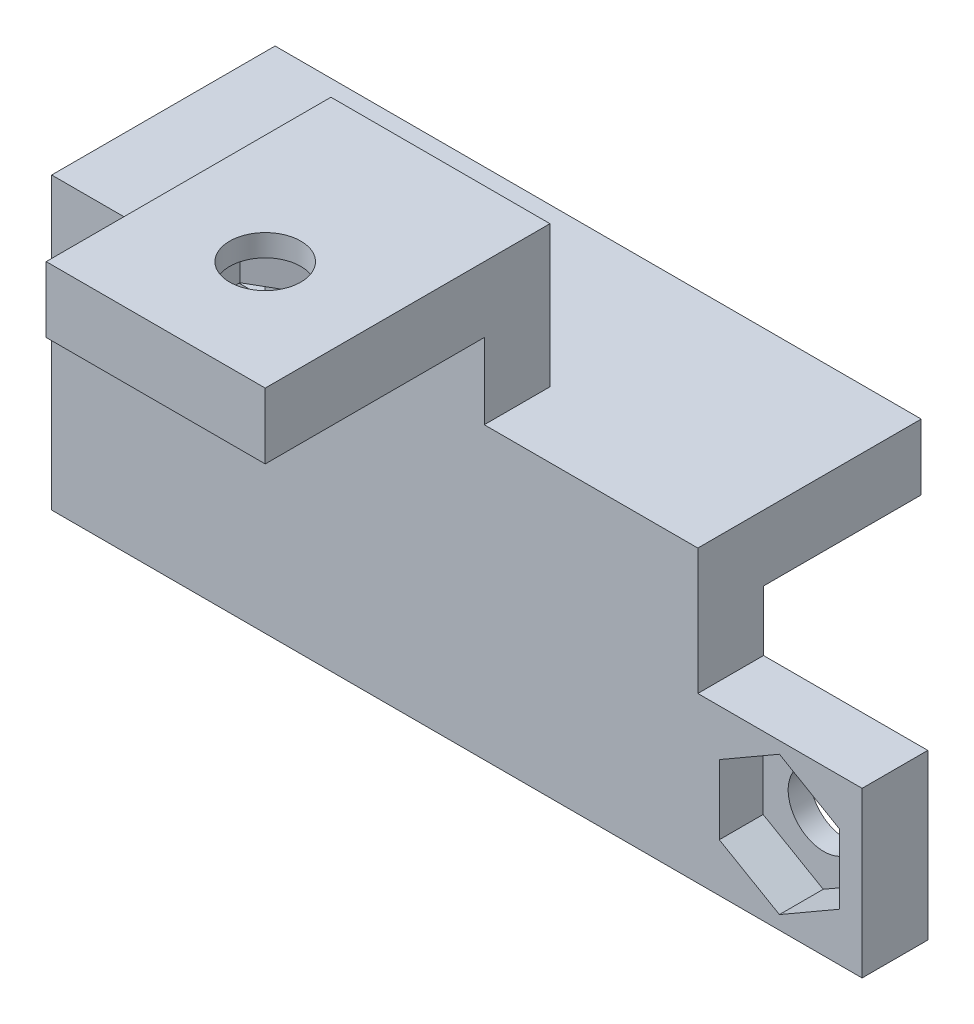
SolidWorks part; units mm, degrees
ref_plane "Alzado" through (0, 0, 0) normal (0, 0, 1) x (1, 0, 0)
ref_plane "Planta" through (0, 0, 0) normal (0, 1, 0) x (1, 0, 0)
ref_plane "Vista lateral" through (0, 0, 0) normal (1, 0, 0) x (0, 0, -1)
sketch "Croquis1" plane through (0, 0, 0) normal (0, 0, 1) x (1, 0, 0)
  line L0 (-40.4588, -20.95) -> (-40.4588, -24.7) construction
  line L1 (-40.4588, -24.7) -> (-77.4588, -24.7)
  line L2 (-77.4588, -14.45) -> (-47.9588, -14.45)
  line L4 (-40.4588, -24.7) -> (-40.4588, -17.2)
  line L5 (-40.4588, -17.2) -> (-47.9588, -17.2)
  line L7 (-47.9588, -17.2) -> (-47.9588, -14.45)
  line L8 (-77.4588, -24.7) -> (-77.4588, -14.45)
  circle A0 centre (-44.2088, -20.95) radius 1.625
  dimension "D1" = 3.25
  dimension "D2" = 40.4588
  dimension "D3" = 44.2088
  dimension "D4" = 47.9588
  dimension "D5" = 77.4588
  dimension "D6" = 14.45
  dimension "D7" = 17.2
extrude "Saliente-Extruir1" add sketch "Croquis1" along normal blind 3
sketch "Croquis2" plane through (0, 0, 3) normal (0, 0, 1) x (1, 0, 0)
  line L0 (-40.4588, -24.7) -> (-40.4588, -17.2) construction
  line L1 (-44.2325, -17.739) -> (-46.9778, -19.324)
  line L2 (-46.9778, -19.324) -> (-46.9778, -22.494)
  line L3 (-46.9778, -22.494) -> (-44.2325, -24.079)
  line L4 (-44.2325, -24.079) -> (-41.4872, -22.494)
  line L5 (-41.4872, -22.494) -> (-41.4872, -19.324)
  line L6 (-41.4872, -19.324) -> (-44.2325, -17.739)
  line L7 (-47.9588, -14.45) -> (-77.4588, -14.45) construction
  circle A0 centre (-44.2325, -20.909) radius 2.7453 construction
  dimension "D1" = 5.4906
  dimension "D2" = 1.0284
  dimension "D3" = 3.289
extrude "Cortar-Extruir1" cut sketch "Croquis2" against normal blind 2
sketch "Croquis4" plane through (0, -14.45, 0) normal (0, 1, 0) x (1, 0, 0)
  line L0 (-77.3588, 7.2) -> (-77.4588, 7.2) construction
  line L1 (-77.4588, -3) -> (-77.4588, 0) construction
  line L2 (-47.9588, -3) -> (-77.4588, -3)
  line L3 (-47.9588, -3) -> (-47.9588, 7.2)
  line L4 (-47.9588, 7.2) -> (-77.4588, 7.2)
  line L5 (-77.4588, -3) -> (-77.4588, 7.2)
  line L6 (-47.9588, 0) -> (-77.4588, 0) construction
  dimension "D1" = 29.5
  dimension "D2" = 7.2
  dimension "D3" = 3
extrude "Saliente-Extruir2" add sketch "Croquis4" along normal blind 3
sketch "Croquis6" plane through (0, 0, 3) normal (0, 0, 1) x (1, 0, 0)
  line L0 (-77.4588, -11.45) -> (-47.9588, -11.45) construction
  line L1 (-47.9588, -11.45) -> (-62.7088, -11.45) construction
  line L2 (-47.9588, -17.2) -> (-47.9588, -11.45) construction
  line L3 (-62.7088, -11.45) -> (-62.7088, -5) construction
  line L4 (-62.7088, -11.45) -> (-67.7088, -11.45)
  line L5 (-62.7088, -11.45) -> (-57.7088, -11.45)
  line L6 (-57.7088, -11.45) -> (-57.7088, -5)
  line L7 (-57.7088, -5) -> (-67.7088, -5)
  line L8 (-67.7088, -5) -> (-67.7088, -11.45)
  line L9 (-46.9778, -19.324) -> (-46.9778, -22.494) construction
  dimension "D1" = 10.731
  dimension "D2" = 12.739
extrude "Saliente-Extruir3" add sketch "Croquis6" against normal up to vertex (3 mm away)
sketch "Croquis7" plane through (0, -5, 0) normal (0, 1, 0) x (1, 0, 0)
  line L0 (-57.7088, 0) -> (-67.7088, 0) construction
  line L1 (-67.7088, 0) -> (-57.7088, 0)
  line L2 (-67.7088, 0) -> (-67.7088, -3)
  line L3 (-67.7088, -3) -> (-57.7088, -3)
  line L4 (-57.7088, 0) -> (-57.7088, -3)
  line L5 (-57.7088, 0) -> (-57.7088, -3) construction
  line L6 (-57.7088, -3) -> (-67.7088, -3) construction
  dimension "D1" = 10
extrude "Saliente-Extruir4" add sketch "Croquis7" along normal up to vertex (5 mm away)
sketch "Croquis9" plane through (0, 0, 3) normal (0, 0, 1) x (1, 0, 0)
  line L0 (-57.2795, -5) -> (-59.2014, -5) construction
  line L1 (-57.7088, -8) -> (-57.7088, -5)
  line L2 (-57.7088, -11.45) -> (-57.7088, 0) construction
  line L3 (-57.7088, -8) -> (-67.7088, -8)
  line L4 (-67.7088, 0) -> (-67.7088, -11.45) construction
  line L5 (-67.7088, -8) -> (-67.7088, -5)
  line L6 (-67.7088, -5) -> (-57.7088, -5)
  line L8 (-40.4588, -17.2) -> (-47.9588, -17.2) construction
  dimension "D1" = 9.2
  dimension "D2" = 12.2
extrude "Saliente-Extruir5" add sketch "Croquis9" along normal blind 10
sketch "Croquis10" plane through (0, -8, 0) normal (0, -1, 0) x (1, 0, 0)
  line L0 (-57.7088, 3) -> (-67.7088, 13) construction
  line L1 (-77.4588, 3) -> (-40.4588, 3) construction
  line L2 (-57.7088, 13) -> (-57.7088, 3) construction
  line L3 (-67.7088, 13) -> (-57.7088, 13) construction
  circle A0 centre (-62.7088, 8) radius 1.625
  dimension "D1" = 3.25
  dimension "D2" = 5
extrude "Cortar-Extruir2" cut sketch "Croquis10" against normal up to vertex (3 mm away)
sketch "Croquis11" plane through (0, -8, 0) normal (0, -1, 0) x (1, 0, 0)
  line L0 (-67.7088, 3) -> (-57.7088, 13) construction
  line L1 (-67.7088, 13) -> (-67.7088, 3) construction
  line L2 (-77.4588, 3) -> (-40.4588, 3) construction
  line L3 (-67.7088, 13) -> (-57.7088, 13) construction
  line L4 (-57.7088, 13) -> (-57.7088, 3) construction
  line L5 (-62.7088, 4.83) -> (-59.9635, 6.415)
  line L6 (-59.9635, 6.415) -> (-59.9635, 9.585)
  line L7 (-59.9635, 9.585) -> (-62.7088, 11.17)
  line L8 (-62.7088, 11.17) -> (-65.4541, 9.585)
  line L9 (-65.4541, 9.585) -> (-65.4541, 6.415)
  line L10 (-65.4541, 6.415) -> (-62.7088, 4.83)
  circle A0 centre (-62.7088, 8) radius 2.7453 construction
  dimension "D1" = 5.4906
  dimension "D2" = 2.2547
extrude "Cortar-Extruir3" cut sketch "Croquis11" against normal blind 2
sketch "Croquis12" plane through (-57.7088, 0, 0) normal (1, 0, 0) x (0, 0, -1)
  line L0 (-3, 0) -> (0, 0) construction
  line L1 (0, 0) -> (-3, 0)
  line L2 (0, 0) -> (0, -5)
  line L3 (0, -5) -> (-3, -5)
  line L4 (-3, 0) -> (-3, -5)
  line L5 (-3, -5) -> (-3, 0) construction
  line L6 (0, -11.45) -> (0, 0) construction
  line L7 (0, -11.45) -> (-3, -11.45) construction
  dimension "D1" = 6.45
extrude "Cortar-Extruir4" cut sketch "Croquis12" against normal up to vertex
